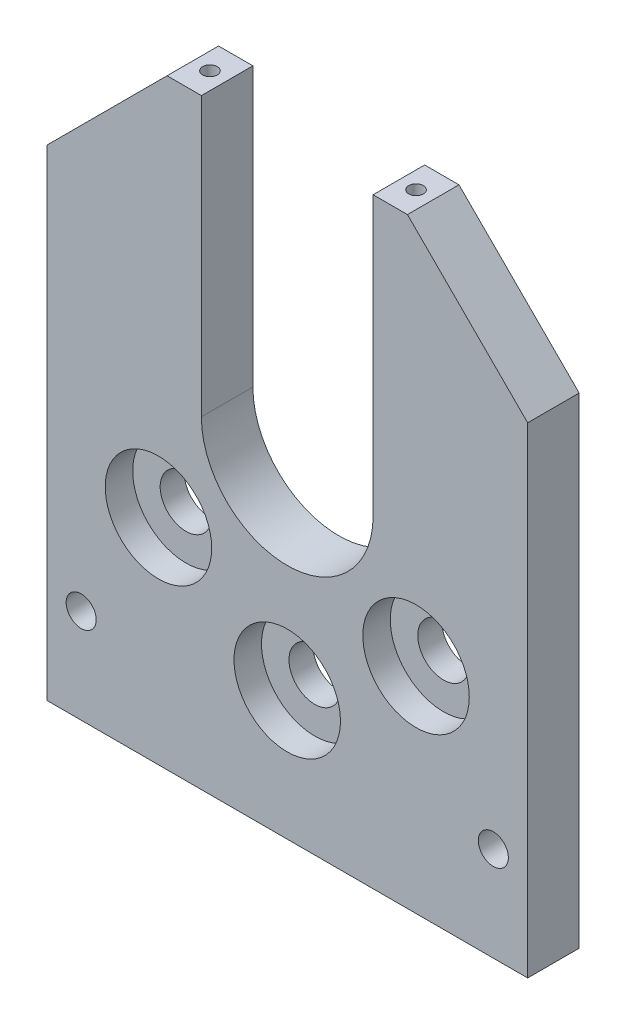
SolidWorks part; units mm, degrees
material "Alloy Steel"
ref_plane "Front Plane" through (0, 0, 0) normal (0, 0, 1) x (1, 0, 0)
ref_plane "Top Plane" through (0, 0, 0) normal (0, 1, 0) x (1, 0, 0)
ref_plane "Right Plane" through (0, 0, 0) normal (1, 0, 0) x (0, 0, -1)
sketch "Sketch2" plane through (0, 0, 0) normal (0, 1, 0) x (1, 0, 0)
  line L1 (-140, 15) -> (140, 15)
  line L2 (-140, 15) -> (-140, -15)
  line L3 (-140, -15) -> (140, -15)
  line L4 (140, 15) -> (140, -15)
  line L5 (-140, 15) -> (140, -15) construction
  line L6 (-140, -15) -> (140, 15) construction
  point P0 (0, 0)
  dimension "D1" = 280
  dimension "D2" = 30
extrude "Boss-Extrude2" add sketch "Sketch2" along normal blind 350 contours L3 L4 L1 L2
sketch "Sketch4" plane through (0, 0, 15) normal (0, 0, 1) x (1, 0, 0)
  line L0 (0, 402.3783) -> (0, -61.9521)
  line L1 (0, 350) -> (0, 188) construction
  line L2 (-140, 350) -> (140, 350) construction
  line L3 (50, 350) -> (50, 188)
  line L4 (-50, 350) -> (-50, 188)
  arc A0 (50, 350) -> (-50, 350) centre (0, 350) ccw
  arc A1 (-50, 188) -> (50, 188) centre (0, 188) ccw
  point P7 (0, 269)
  line M5 (140, 350) -> (-140, 350)
  dimension "D1" = 100
  dimension "D2" = 162
extrude "Cut-Extrude1" cut sketch "Sketch4" against normal blind 350 contours L0 A1 L3 M5 | L4 A1 L0 M5 | L0 A0 M5 | A0 L0 M5
chamfer "Chamfer1" distance 70 angle 45 2 edges at (-140, 350, 0) (140, 350, 0)
sketch "Sketch6" plane through (0, 350, 0) normal (0, 1, 0) x (1, 0, 0)
  line L0 (-154, 0) -> (154, 0) construction
  point P0 (-60, 0)
  point P1 (60, 0)
  dimension "D1" = 60
  dimension "D2" = 60
hole_wizard "M10 Tapped Hole1" positions "3DSketch1" profile "Sketch7" tap size "M10" standard "ISO"
sketch3d "3DSketch1"
  point P0 (-60, 350, 0)
  point P3 (60, 350, 0)
sketch "Sketch7" plane through (-60, 350, 0) normal (1, 0, 0) x (0, 0, 1)
  line L0 (0, 0) -> (0, 28.25)
  line L1 (0, 28.25) -> (4.25, 24)
  line L2 (4.25, 24) -> (4.25, 0)
  line L5 (4.25, 0) -> (0, 0)
  line L10 (0, 28.25) -> (-4.25, 24) construction
  line L11 (0, -6.35) -> (0, 107.95) construction
  dimension "Tap Drill Dia." = 8.5
  dimension "Tap Drill Depth" = 24
  dimension "Drill Angle" = 90
cosmetic thread "Hole Thread1" parameters "D1"=24, "D2"=10
cosmetic thread "Hole Thread2" parameters "D1"=24, "D2"=10
sketch "Sketch8" plane through (0, 0, 15) normal (0, 0, 1) x (1, 0, 0)
  line L0 (16.5, 0) -> (-16.5, 0) construction
  line L1 (-140, 280) -> (-140, 0) construction
  line L2 (140, 280) -> (140, 0) construction
  circle A0 centre (-120, 55) radius 8.75
  circle A1 centre (120, 55) radius 8.75
  dimension "D1" = 17.5
  dimension "D2" = 55
  dimension "D3" = 20
  dimension "D4" = 20
extrude "Cut-Extrude2" cut sketch "Sketch8" against normal blind 350
sketch "Sketch9" plane through (0, 0, 15) normal (0, 0, 1) x (1, 0, 0)
  line L0 (0, -16.5) -> (0, 16.5) construction
  line L2 (16.5, 0) -> (-16.5, 0) construction
  circle A0 centre (-75, 124.7494) radius 15
  circle A1 centre (75, 124.7494) radius 15
  circle A2 centre (0, 75) radius 15
  dimension "D1" = 30
  dimension "D4" = 75
  dimension "D2" = 90
  dimension "D3" = 75
  dimension "D5" = 90
extrude "Cut-Extrude3" cut sketch "Sketch9" against normal blind 350
sketch "Sketch10" plane through (0, 0, 15) normal (0, 0, 1) x (1, 0, 0)
  circle A0 centre (-75, 124.7494) radius 31
  circle A1 centre (0, 75) radius 31
  circle A2 centre (75, 124.7494) radius 31
  dimension "D1" = 62
extrude "Cut-Extrude4" cut sketch "Sketch10" against normal blind 16
